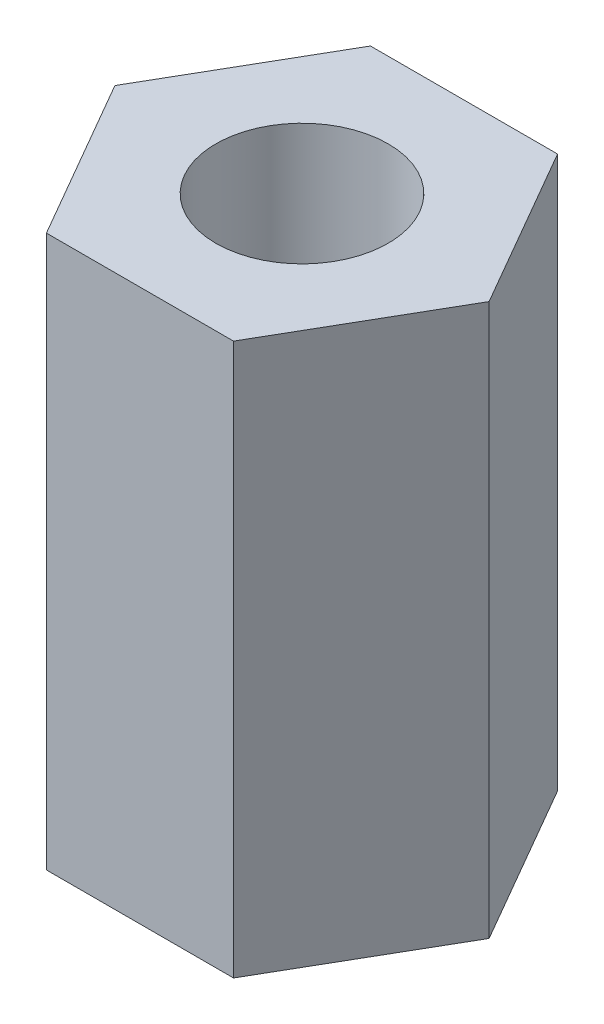
SolidWorks part; units mm, degrees
material "Nylon 101"
ref_plane "Front Plane" through (0, 0, 0) normal (0, 0, 1) x (1, 0, 0)
ref_plane "Top Plane" through (0, 0, 0) normal (0, 1, 0) x (1, 0, 0)
ref_plane "Right Plane" through (0, 0, 0) normal (1, 0, 0) x (0, 0, -1)
sketch "Sketch1" plane through (0, 0, 0) normal (0, 1, 0) x (1, 0, 0)
  line L1 (2.7135, 0) -> (1.3568, 2.35)
  line L2 (1.3568, 2.35) -> (-1.3568, 2.35)
  line L3 (-1.3568, 2.35) -> (-2.7135, 0)
  line L4 (-2.7135, 0) -> (-1.3568, -2.35)
  line L5 (-1.3568, -2.35) -> (1.3568, -2.35)
  line L6 (1.3568, -2.35) -> (2.7135, 0)
  circle A0 centre (0, 0) radius 2.35 construction
  circle A1 centre (0, 0) radius 1.25
  dimension "D2" = 2.5
  dimension "D1" = 4.7
extrude "Boss-Extrude1" add sketch "Sketch1" along normal blind 8
